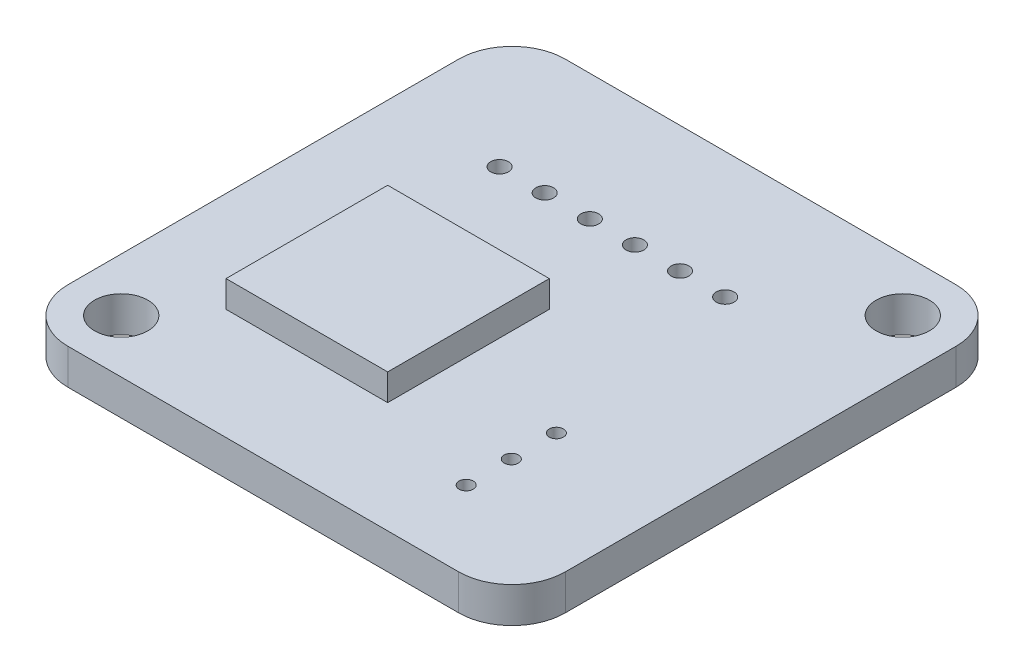
SolidWorks part; units mm, degrees
ref_plane "Plan de face" through (0, 0, 0) normal (0, 0, 1) x (1, 0, 0)
ref_plane "Plan de dessus" through (0, 0, 0) normal (0, 1, 0) x (1, 0, 0)
ref_plane "Plan de droite" through (0, 0, 0) normal (1, 0, 0) x (0, 0, -1)
sketch "Esquisse2" plane through (0, 0, 0) normal (0, 1, 0) x (1, 0, 0)
  line L0 (0, -3) -> (22, -3)
  line L1 (0, 0) -> (22, 0) construction
  line L2 (0, 0) -> (0, 22) construction
  line L3 (0, 22) -> (22, 22) construction
  line L4 (22, 0) -> (22, 22) construction
  line L5 (25, 0) -> (25, 22)
  line L6 (0, 25) -> (22, 25)
  line L7 (-3, 0) -> (-3, 22)
  line L8 (-3, -3) -> (25, -3) construction
  line L9 (25, -3) -> (25, 25) construction
  line L10 (-3, 25) -> (25, 25) construction
  line L11 (-3, -3) -> (-3, 25) construction
  circle A0 centre (0, 0) radius 1.5
  arc A1 (22, -3) -> (25, 0) centre (22, 0) ccw
  circle A2 centre (22, 22) radius 1.5
  arc A3 (25, 22) -> (22, 25) centre (22, 22) ccw
  arc A4 (0, -3) -> (-3, 0) centre (0, 0) cw
  arc A5 (-3, 22) -> (0, 25) centre (0, 22) cw
  dimension "D2" = 22
  dimension "D4" = 3
  dimension "D5" = 0
  dimension "D1" = 3
  dimension "D3" = 22
extrude "Boss.-Extru.1" add sketch "Esquisse2" along normal blind 2
sketch "Esquisse3" plane through (0, 2, 0) normal (0, 1, 0) x (1, 0, 0)
  line L0 (22, 25) -> (0, 25) construction
  line L1 (-3, 22) -> (-3, 0) construction
  circle A0 centre (5.94, 17.9) radius 0.5
  circle A1 centre (8.48, 17.9) radius 0.5
  circle A2 centre (11.02, 17.9) radius 0.5
  circle A3 centre (13.56, 17.9) radius 0.5
  circle A4 centre (16.1, 17.9) radius 0.5
  circle A20 centre (3.4, 17.9) radius 0.5
  point P0 (11, 25)
  dimension "D1" = 7.1
  dimension "D2" = 6.4
extrude "Enlèv. mat.-Extru.1" cut sketch "Esquisse3" against normal up to next
sketch "Esquisse4" plane through (0, 2, 0) normal (0, 1, 0) x (1, 0, 0)
  line L0 (2.65, 12.35) -> (2.65, 3.25)
  line L1 (-3, 22) -> (-3, 0) construction
  line L2 (22, 25) -> (0, 25) construction
  line L5 (2.65, 3.25) -> (11.75, 3.25)
  line L6 (11.75, 12.35) -> (11.75, 3.25)
  line L7 (2.65, 12.35) -> (11.75, 12.35)
  dimension "D1" = 5.65
  dimension "D2" = 12.65
  dimension "D3" = 9.1
  dimension "D4" = 9.1
extrude "Boss.-Extru.2" add sketch "Esquisse4" along normal blind 1.5
sketch "Esquisse5" plane through (0, 2, 0) normal (0, 1, 0) x (1, 0, 0)
  line L0 (25, 0) -> (25, 22) construction
  line L1 (0, -3) -> (22, -3) construction
  circle A0 centre (17.98, 1.44) radius 0.4
  circle A1 centre (17.98, 3.98) radius 0.4
  circle A2 centre (17.98, 6.52) radius 0.4
  dimension "D1" = 7.02
  dimension "D2" = 4.44
  dimension "D3" = 3
  dimension "D4" = 2.54
extrude "Enlèv. mat.-Extru.2" cut sketch "Esquisse5" against normal up to next
